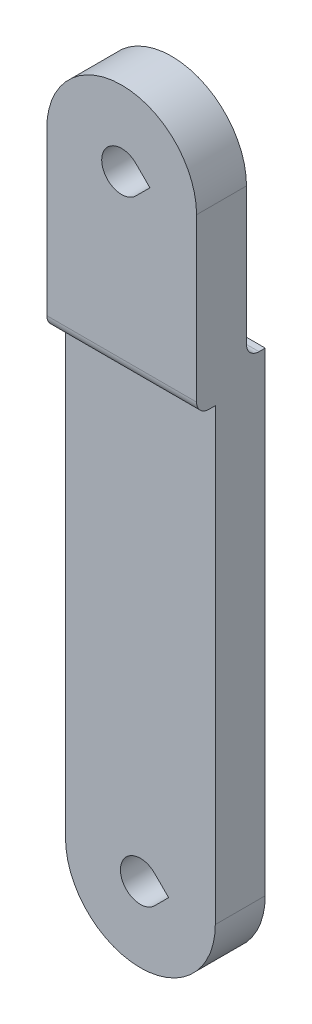
SolidWorks part; units mm, degrees
ref_plane "前视基准面" through (0, 0, 0) normal (0, 0, 1) x (1, 0, 0)
ref_plane "上视基准面" through (0, 0, 0) normal (0, 1, 0) x (1, 0, 0)
ref_plane "右视基准面" through (0, 0, 0) normal (1, 0, 0) x (0, 0, -1)
sketch "草图1" plane through (0, 0, 0) normal (0, 0, 1) x (1, 0, 0)
  line L0 (0, 140.066) -> (0, -140.066) construction
  line L1 (-140.066, 0) -> (140.066, 0) construction
  line L2 (0, 50) -> (0, 0) construction
  line L3 (6, 50) -> (6, 0)
  line L4 (-6, 50) -> (-6, 0)
  line L5 (0, 50) -> (2.2627, 50) construction
  line L6 (2.2627, 50) -> (1.1314, 51.1314)
  line L7 (2.2627, 50) -> (1.1314, 48.8686)
  line L8 (0, 25) -> (38.3725, 25) construction
  line L9 (2.2627, 0) -> (1.1314, 1.1314)
  line L10 (2.2627, 0) -> (1.1314, -1.1314)
  arc A0 (1.1314, 1.1314) -> (1.1314, -1.1314) centre (0, 0) ccw
  arc A1 (1.1314, 51.1314) -> (1.1314, 48.8686) centre (0, 50) ccw
  arc A2 (6, 50) -> (-6, 50) centre (0, 50) ccw
  arc A3 (-6, 0) -> (6, 0) centre (0, 0) ccw
  point P9 (0, 25)
  dimension "D1" = 50
  dimension "D2" = 3.2
  dimension "D3" = 6
  dimension "D4" = 45
extrude "凸台-拉伸1" add sketch "草图1" along normal mid plane 22
sketch "草图2" plane through (6, 0, 0) normal (1, 0, 0) x (0, 0, -1)
  line L0 (-7, 56) -> (-7, 38)
  line L1 (11, 56) -> (-11, 56) construction
  line L2 (-7, 38) -> (7, 38)
  line L3 (7, 38) -> (7, 56)
  line L4 (7, 56) -> (-7, 56)
  line L5 (-11, 0) -> (-11, 50) construction
  line L6 (11, 0) -> (11, 50) construction
  line L7 (-11, 25) -> (53.7143, 25) construction
  line L12 (-5.5, -6) -> (-5.5, 35)
  line L19 (-11, -6) -> (11, -6) construction
  line L20 (-5.5, 35) -> (5.5, 35)
  line L21 (5.5, 35) -> (5.5, -6)
  line L22 (5.5, -6) -> (-5.5, -6)
  line L23 (-9.5, -6) -> (-9.5, 36)
  line L24 (-9.5, 36) -> (-11, 36)
  line L25 (-11, 36) -> (-11, -6)
  line L26 (-11, -6) -> (-9.5, -6)
  line L27 (0, 0) -> (0, 65.1013) construction
  line L29 (-11, 0) -> (11, 0) construction
  line L30 (11, -6) -> (9.5, -6)
  line L31 (11, 36) -> (11, -6)
  line L32 (9.5, 36) -> (11, 36)
  line L33 (9.5, -6) -> (9.5, 36)
  point P16 (0, 25)
  dimension "D1" = 4
  dimension "D2" = 4
  dimension "D3" = 18
  dimension "D4" = 2
  dimension "D5" = 3
  dimension "D7" = 5.5
  dimension "D9" = 5.5
  dimension "D10" = 4
  dimension "D12" = 14
extrude "切除-拉伸1" cut sketch "草图2" against normal blind 28
fillet "圆角1" radius 1 4 edges at (0, 38, 7) (0, 38, -7) (0, 36, -11) (0, 36, 11)
sketch "草图3" plane through (0, 0, 5.5) normal (0, 0, -1) x (-1, 0, 0)
  line L1 (-64.0828, -21.2547) -> (68.2262, -21.2547)
  line L2 (-64.0828, -21.2547) -> (-64.0828, 73.7645)
  line L3 (-64.0828, 73.7645) -> (68.2262, 73.7645)
  line L4 (68.2262, -21.2547) -> (68.2262, 73.7645)
extrude "切除-拉伸2" cut sketch "草图3" along normal blind 76
